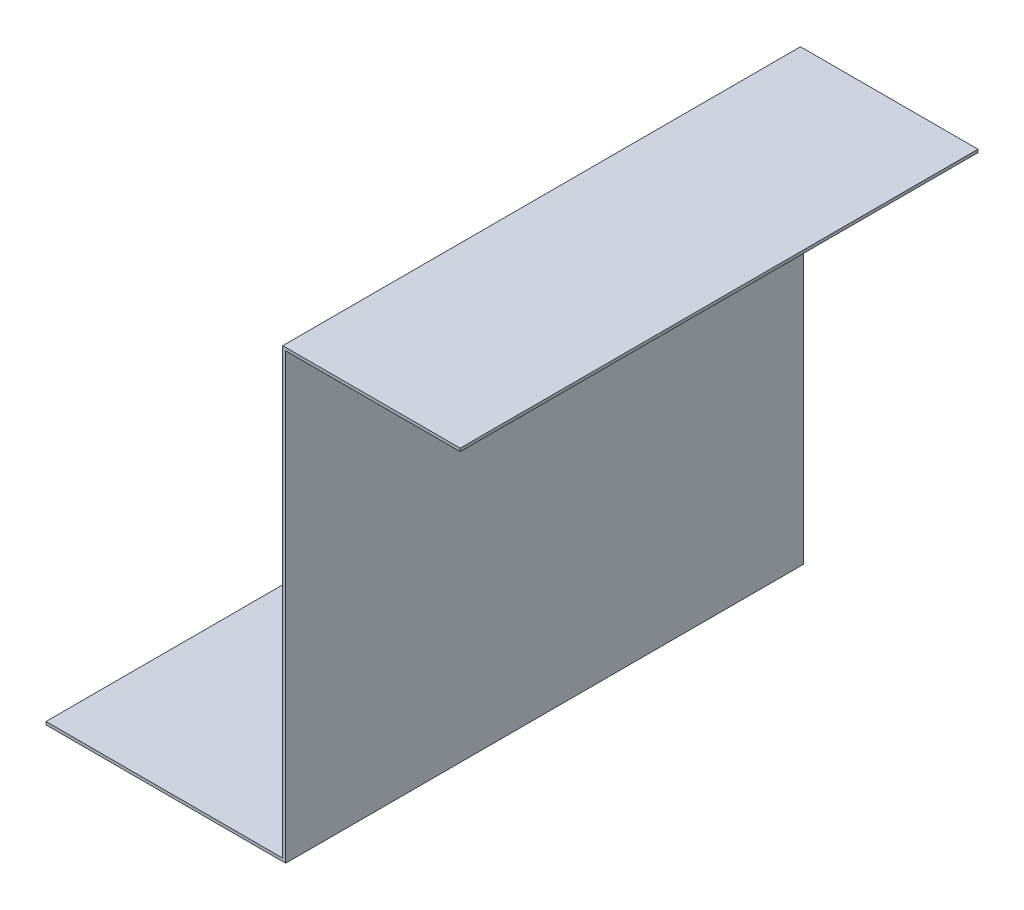
SolidWorks part; units mm, degrees
ref_plane "Front Plane" through (0, 0, 0) normal (0, 0, 1) x (1, 0, 0)
ref_plane "Top Plane" through (0, 0, 0) normal (0, 1, 0) x (1, 0, 0)
ref_plane "Right Plane" through (0, 0, 0) normal (1, 0, 0) x (0, 0, -1)
sketch "Sketch1" plane through (0, 0, 0) normal (0, 1, 0) x (1, 0, 0)
  line L0 (40, 0) -> (-4, 0) construction
  line L1 (-40, -87.5) -> (40, -87.5)
  line L2 (-40, -87.5) -> (-40, 87.5)
  line L3 (-40, 87.5) -> (40, 87.5)
  line L4 (40, -87.5) -> (40, 87.5)
  line L5 (-40, -87.5) -> (40, 87.5) construction
  line L6 (-40, 87.5) -> (40, -87.5) construction
  line L7 (-4, 0) -> (-4, 19.6) construction
  circle A0 centre (-4, 19.6) radius 2.5
  circle A1 centre (-4, -19.6) radius 2.5
  point P0 (0, 0)
  dimension "D5" = 5
  dimension "D1" = 80
  dimension "D2" = 175
  dimension "D3" = 44
  dimension "D4" = 19.6
extrude "Boss-Extrude1" add sketch "Sketch1" along normal blind 1
sketch "Sketch2" plane through (40, 0, 0) normal (1, 0, 0) x (0, 0, -1)
  line L1 (-87.5, 0) -> (87.5, 0)
  line L2 (-87.5, 0) -> (-87.5, 150)
  line L3 (-87.5, 150) -> (87.5, 150)
  line L4 (87.5, 0) -> (87.5, 150)
  point P5 (0, 0)
  point P7 (0, 0)
  dimension "D1" = 150
extrude "Boss-Extrude2" add sketch "Sketch2" along normal blind 1
sketch "Sketch3" plane through (0, 150, 0) normal (0, 1, 0) x (1, 0, 0)
  line L1 (40, 87.5) -> (100, 87.5)
  line L2 (40, 87.5) -> (40, -87.5)
  line L3 (40, -87.5) -> (100, -87.5)
  line L4 (100, 87.5) -> (100, -87.5)
  point P5 (0, 0)
  dimension "D1" = 60
extrude "Boss-Extrude3" add sketch "Sketch3" along normal blind 1
